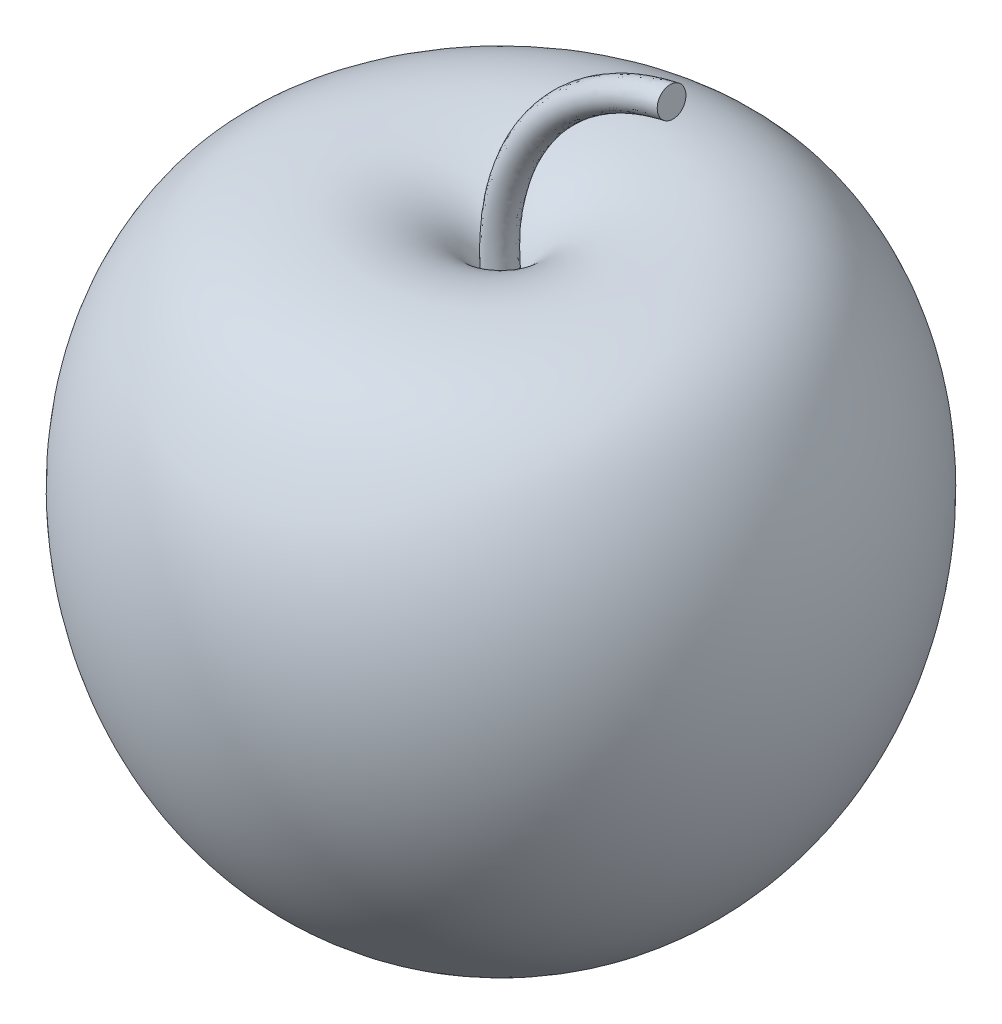
SolidWorks part; units mm, degrees
ref_plane "Ön Düzlem" through (0, 0, 0) normal (0, 0, 1) x (1, 0, 0)
ref_plane "Üst Düzlem" through (0, 0, 0) normal (0, 1, 0) x (1, 0, 0)
ref_plane "Sağ Düzlem" through (0, 0, 0) normal (1, 0, 0) x (0, 0, -1)
sketch "Çizim1" plane through (0, 0, 0) normal (0, 0, 1) x (1, 0, 0)
  line L0 (0, 0) -> (0, -75)
  line L1 (0, 0) -> (-2, 0)
  line L2 (43.1334, -75) -> (-43.1334, -75) construction
  line L3 (-45, -10.031) -> (-45, -58.735) construction
  spline S0 degree 3 poles (-2, 0) (-5.7939, 9.3835) (-27.766, 11.2279) (-57.1319, -20.0115) (-39.8678, -75) (0, -75) knots 0 0 0 0 0.180103 0.280103 1 1 1 1
  dimension "D3" = 45
  dimension "D1" = 75
  dimension "D2" = 2
revolve "Döndür1" add sketch "Çizim1" angle 360 about L0
sketch "Çizim2" plane through (0, 0, 0) normal (0, 0, 1) x (1, 0, 0)
  arc A0 (0, 0) -> (23.8786, 33.3188) centre (30.4081, 3.4234) cw
sketch "Çizim3" plane through (0, 0, 0) normal (0, 1, 0) x (1, 0, 0)
  circle A0 centre (0, 0) radius 2
sweep "Süpür1" add profiles "Çizim3" path "Çizim2"
